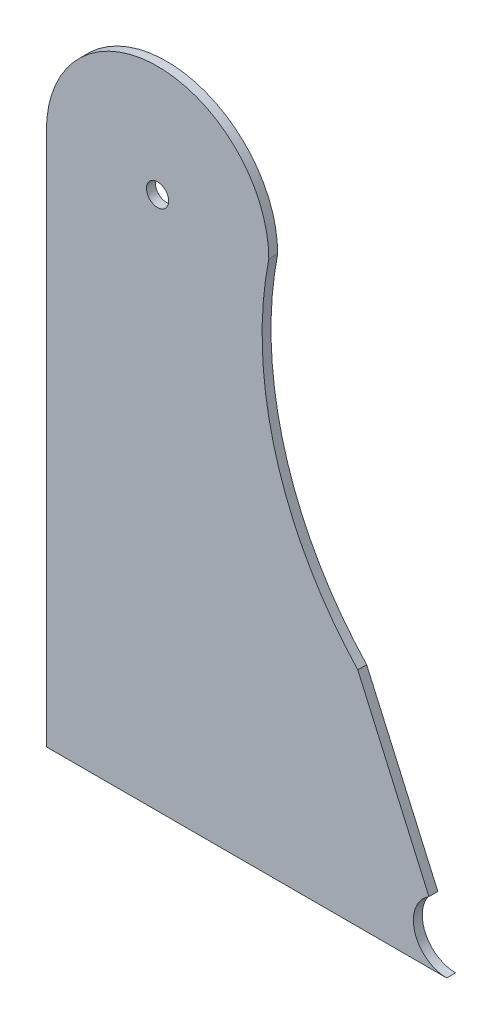
SolidWorks part; units mm, degrees
ref_plane "Front Plane" through (0, 0, 0) normal (0, 0, 1) x (1, 0, 0)
ref_plane "Top Plane" through (0, 0, 0) normal (0, 1, 0) x (1, 0, 0)
ref_plane "Right Plane" through (0, 0, 0) normal (1, 0, 0) x (0, 0, -1)
sketch "Sketch1" plane through (0, 0, 0) normal (0, 0, 1) x (1, 0, 0)
  line L0 (0, 0) -> (-114.3, 0)
  line L1 (-114.3, 0) -> (-114.3, 152.4)
  line L3 (-114.3, 152.4) -> (-50.8, 152.4) construction
  line L5 (-5.08, 17.5822) -> (-25.4, 63.5)
  arc A0 (-114.3, 152.4) -> (-50.8, 152.4) centre (-82.55, 152.4) cw
  arc A1 (-50.8, 152.4) -> (-25.4, 63.5) centre (48.8925, 132.805) ccw
  arc A2 (-5.08, 17.5822) -> (0, 0) centre (0, 9.525) ccw
  circle A3 centre (-82.55, 152.4) radius 3.175
  point P8 (0, 0)
  dimension "D5" = 63.5
  dimension "D6" = 101.6
  dimension "D7" = 31.75
  dimension "D4" = 19.05
  dimension "D8" = 6.35
  dimension "D10" = 63.5
  dimension "D1" = 114.3
  dimension "D2" = 152.4
  dimension "D3" = 88.9
  dimension "D9" = 109.22
extrude "Boss-Extrude1" add sketch "Sketch1" along normal blind 2.54
